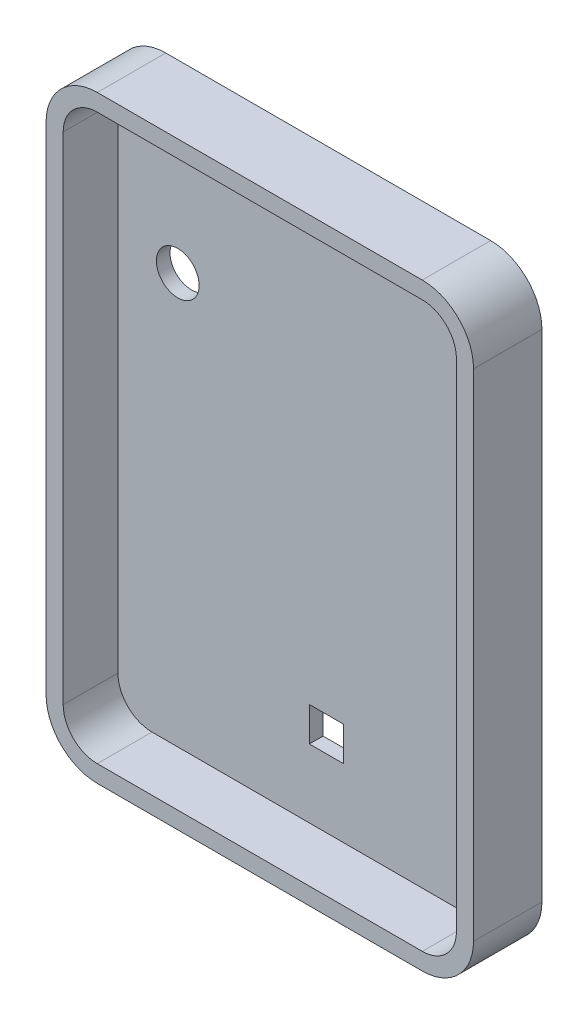
SolidWorks part; units mm, degrees
ref_plane "Front Plane" through (0, 0, 0) normal (0, 0, 1) x (1, 0, 0)
ref_plane "Top Plane" through (0, 0, 0) normal (0, 1, 0) x (1, 0, 0)
ref_plane "Right Plane" through (0, 0, 0) normal (1, 0, 0) x (0, 0, -1)
sketch "Sketch1" plane through (0, 0, 0) normal (0, 0, 1) x (1, 0, 0)
  line L1 (0, 0) -> (63.5, 0)
  line L2 (0, 0) -> (0, -88.9)
  line L3 (0, -88.9) -> (63.5, -88.9)
  line L4 (63.5, 0) -> (63.5, -88.9)
  dimension "D1" = 63.5
  dimension "D2" = 88.9
extrude "Boss-Extrude1" add sketch "Sketch1" along normal blind 10.16
fillet "Fillet1" radius 7.62 4 edges at (0, -88.9, 5.08) (63.5, -88.9, 5.08) (63.5, 0, 5.08) (0, 0, 5.08)
sketch "Sketch2" plane through (0, 0, 10.16) normal (0, 0, 1) x (1, 0, 0)
  line L0 (7.62, -2.54) -> (55.88, -2.54)
  line L1 (60.96, -7.62) -> (60.96, -81.2964)
  line L2 (63.5, -81.28) -> (63.5, -7.62) construction
  line L3 (55.88, 0) -> (7.62, 0) construction
  line L4 (55.8964, -86.36) -> (7.6036, -86.36)
  line L5 (7.62, -88.9) -> (55.88, -88.9) construction
  line L6 (2.54, -7.62) -> (2.54, -81.2964)
  line L7 (0, -7.62) -> (0, -81.28) construction
  arc A0 (2.54, -7.62) -> (7.62, -2.54) centre (7.62, -7.62) cw
  arc A1 (55.88, -2.54) -> (60.96, -7.62) centre (55.88, -7.62) cw
  arc A2 (60.96, -81.2964) -> (55.8964, -86.36) centre (55.8964, -81.2964) cw
  arc A3 (7.6036, -86.36) -> (2.54, -81.2964) centre (7.6036, -81.2964) cw
  dimension "D1" = 2.54
  dimension "D2" = 2.54
  dimension "D3" = 2.54
  dimension "D4" = 2.54
extrude "Cut-Extrude1" cut sketch "Sketch2" against normal blind 8.128
sketch "Sketch3" plane through (0, 0, 0) normal (0, 0, -1) x (-1, 0, 0)
  line L0 (-55.88, 0) -> (-7.62, 0) construction
  line L1 (-58.42, -5.08) -> (-5.08, -5.08)
  line L2 (-58.42, -5.08) -> (-58.42, -83.82)
  line L3 (-58.42, -83.82) -> (-5.08, -83.82)
  line L4 (-5.08, -5.08) -> (-5.08, -83.82)
  line L5 (-63.5, -81.28) -> (-63.5, -7.62) construction
  line L7 (-36.068, -71.12) -> (-30.988, -71.12)
  line L8 (-36.068, -71.12) -> (-36.068, -76.2)
  line L9 (-36.068, -76.2) -> (-30.988, -76.2)
  line L10 (-30.988, -71.12) -> (-30.988, -76.2)
  circle A0 centre (-11.43, -25.4) radius 3.175
  point P14 (0, 0)
  dimension "D10" = 6.35
  dimension "D1" = 5.08
  dimension "D2" = 5.08
  dimension "D3" = 78.74
  dimension "D4" = 53.34
  dimension "D5" = 22.352
  dimension "D6" = 7.62
  dimension "D7" = 5.08
  dimension "D8" = 5.08
  dimension "D9" = 20.32
  dimension "D11" = 6.35
extrude "Cut-Extrude2" cut sketch "Sketch3" against normal blind 12.7 contours L10 L7 L8 L9 | A0
